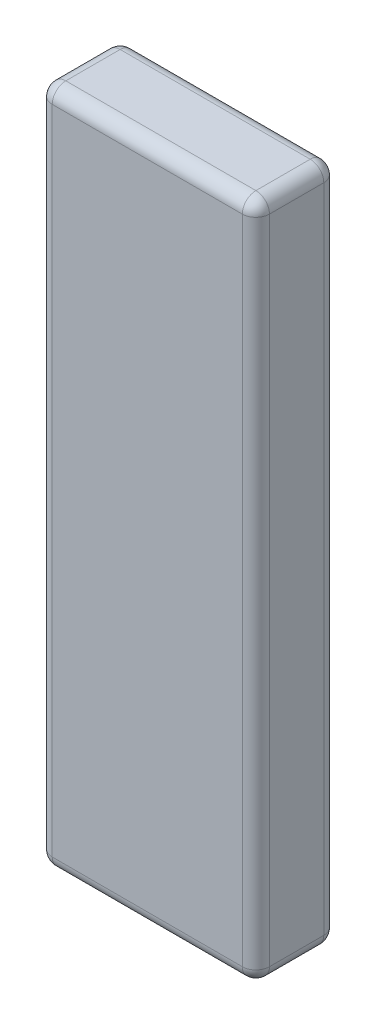
SolidWorks part; units mm, degrees
ref_plane "Front Plane" through (0, 0, 0) normal (0, 0, 1) x (1, 0, 0)
ref_plane "Top Plane" through (0, 0, 0) normal (0, 1, 0) x (1, 0, 0)
ref_plane "Right Plane" through (0, 0, 0) normal (1, 0, 0) x (0, 0, -1)
sketch "Sketch1" plane through (0, 0, 0) normal (0, 0, 1) x (1, 0, 0)
  line L1 (10.16, -31.75) -> (-10.16, -31.75)
  line L2 (10.16, -31.75) -> (10.16, 31.75)
  line L3 (10.16, 31.75) -> (-10.16, 31.75)
  line L4 (-10.16, -31.75) -> (-10.16, 31.75)
  line L5 (10.16, -31.75) -> (-10.16, 31.75) construction
  line L6 (10.16, 31.75) -> (-10.16, -31.75) construction
  point P0 (0, 0)
  dimension "D1" = 20.32
  dimension "D2" = 63.5
extrude "Boss-Extrude1" add sketch "Sketch1" along normal blind 7.62
fillet "Fillet1" radius 1.27 12 edges at (0, -31.75, 0) (-10.16, -31.75, 3.81) (-10.16, 0, 0) (0, -31.75, 7.62) (10.16, -31.75, 3.81) (10.16, 0, 0) (0, 31.75, 0) (-10.16, 0, 7.62) (10.16, 0, 7.62) (-10.16, 31.75, 3.81) (0, 31.75, 7.62) (10.16, 31.75, 3.81)
